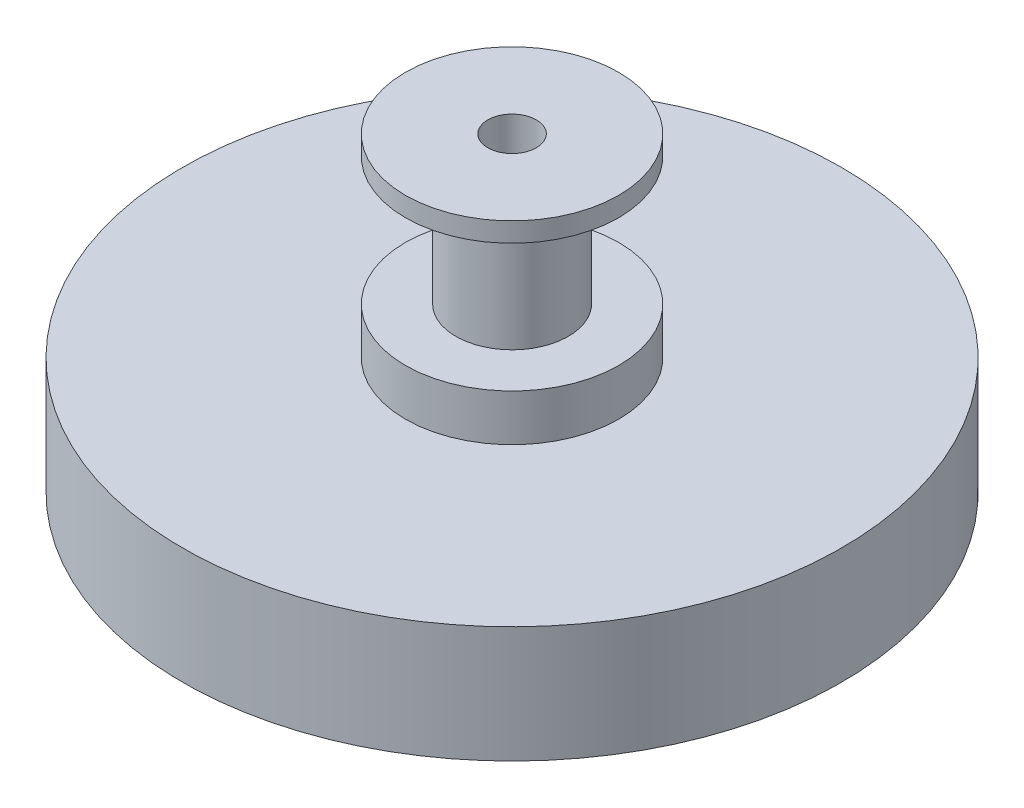
SolidWorks part; units mm, degrees
material "2024-T4"
ref_plane "Front Plane" through (0, 0, 0) normal (0, 0, 1) x (1, 0, 0)
ref_plane "Top Plane" through (0, 0, 0) normal (0, 1, 0) x (1, 0, 0)
ref_plane "Right Plane" through (0, 0, 0) normal (1, 0, 0) x (0, 0, -1)
sketch "Sketch1" plane through (0, 0, 0) normal (1, 0, 0) x (0, 0, -1)
  line L0 (0, -5577.8392) -> (0, 273314.1184) construction
  line L7 (-27.5, 40.7123) -> (-85, 40.7123)
  line L8 (-85, 40.7123) -> (-85, 10.7123)
  line L9 (-85, 10.7123) -> (-6.25, 10.7123)
  line L10 (-6.25, 10.7123) -> (-6.25, 90.7123)
  line L13 (-14.5, 85.7123) -> (-27.5, 85.7123)
  line L14 (-27.5, 85.7123) -> (-27.5, 90.7123)
  line L15 (-27.5, 90.7123) -> (-6.25, 90.7123)
  line L16 (-27.5, 40.7123) -> (-27.5, 52.7123)
  line L17 (-27.5, 52.7123) -> (-14.5, 52.7123)
  line L18 (-14.5, 52.7123) -> (-14.5, 85.7123)
  dimension "D1" = 6.25
  dimension "D2" = 85
  dimension "D3" = 33
  dimension "D4" = 30
  dimension "D5" = 57.5
  dimension "D6" = 80
  dimension "D7" = 12
  dimension "D8" = 13
  dimension "D9" = 78.75
  dimension "D10" = 55
  dimension "D11" = 12
  dimension "D12" = 50
  dimension "D13" = 13
  dimension "D14" = 8.25
revolve "Revolve1" add sketch "Sketch1" angle 360 about L0
